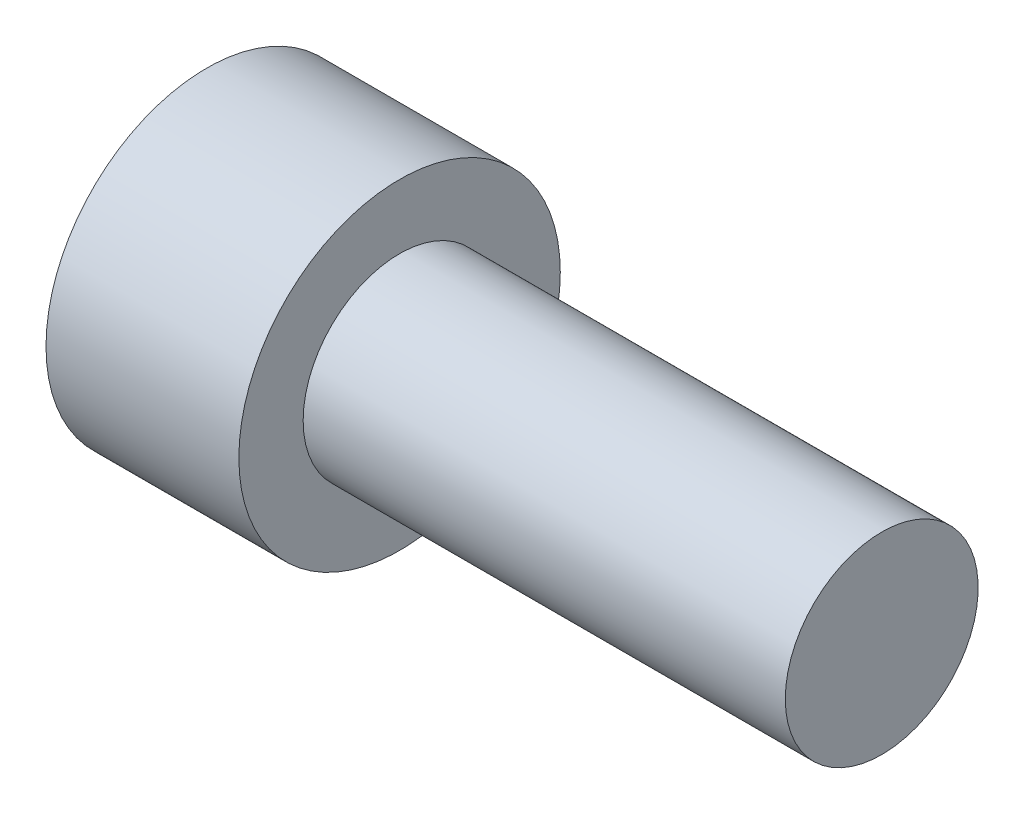
SolidWorks part; units mm, degrees
ref_plane "Front Plane" through (0, 0, 0) normal (0, 0, 1) x (1, 0, 0)
ref_plane "Top Plane" through (0, 0, 0) normal (0, 1, 0) x (1, 0, 0)
ref_plane "Right Plane" through (0, 0, 0) normal (1, 0, 0) x (0, 0, -1)
sketch "Sketch1" plane through (0, 0, 0) normal (0, 0, 1) x (1, 0, 0)
  line L0 (0, 0) -> (21, 0) construction
  line L3 (0, 0) -> (0, 5)
  line L4 (0, 5) -> (6, 5)
  line L5 (6, 3) -> (6, 5)
  line L6 (6, 3) -> (21, 3)
  line L8 (0, 0) -> (21, 0)
  line L9 (21, 3) -> (21, 0)
  dimension "CS_A" = 10
  dimension "CS_E" = 6
  dimension "CS_L" = 15
  dimension "CS_M" = 6
revolve "Revolve1" add sketch "Sketch1" angle 360 about L0
cosmetic thread "Cosmetic Thread1" parameters "CS_D_s"=4.917
sketch "Sketch2" plane through (0, 0, 0) normal (0, 0, 1) x (1, 0, 0)
  line L0 (0, 0) -> (21, 0) construction
  line L1 (0, 5) -> (0, -5) construction
  line L2 (21, -3) -> (21, 3) construction
  line L3 (0, 2.5) -> (3, 2.5)
  line L4 (3, 2.5) -> (4.4434, 0)
  line L5 (0, 2.5) -> (0, 0)
  line L6 (0, 0) -> (4.4434, 0)
  dimension "D1" = 60
  dimension "CS_T_s" = 3
  dimension "CS_B" = 5
revolve "Cut-Revolve1" cut sketch "Sketch2" angle 360 about L0
sketch "Sketch3" plane through (0, 0, 0) normal (-1, 0, 0) x (0, 0, 1)
  line L0 (0, 0) -> (0, 5) construction
  line L1 (0, -2.8868) -> (2.5, -1.4434)
  line L2 (2.5, -1.4434) -> (2.5, 1.4434)
  line L3 (2.5, 1.4434) -> (0, 2.8868)
  line L4 (0, 2.8868) -> (-2.5, 1.4434)
  line L5 (-2.5, 1.4434) -> (-2.5, -1.4434)
  line L6 (-2.5, -1.4434) -> (0, -2.8868)
  circle A0 centre (0, 0) radius 2.5 construction
  circle A1 centre (0, 0) radius 5 construction
  circle A2 centre (0, 0) radius 2.5 construction
extrude "Cut-Extrude1" cut sketch "Sketch3" against normal blind 3
